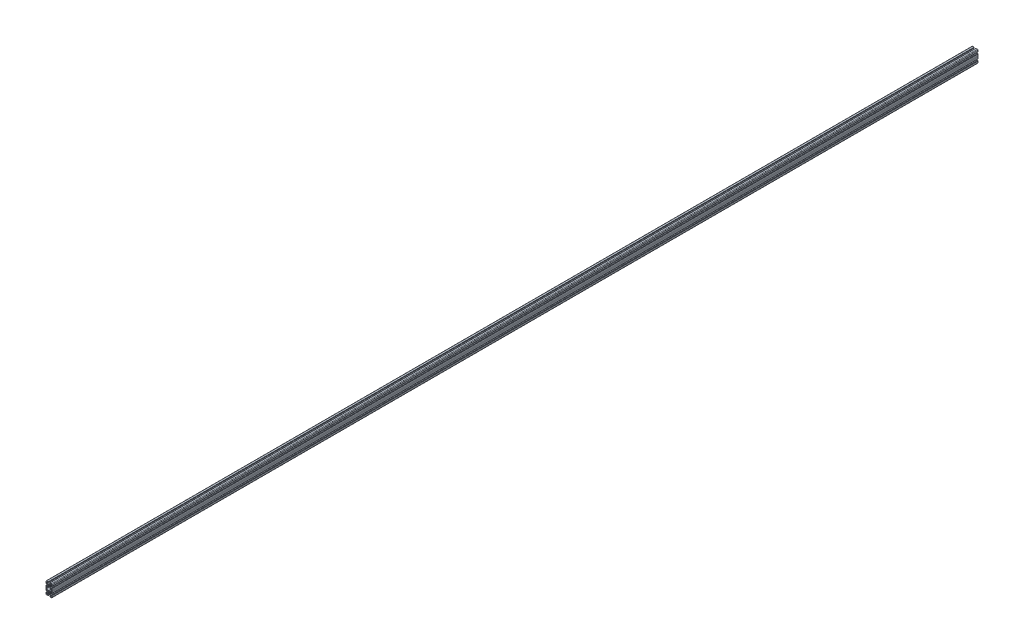
SolidWorks part; units mm, degrees
ref_plane "Front Plane" through (0, 0, 0) normal (0, 0, 1) x (1, 0, 0)
ref_plane "Top Plane" through (0, 0, 0) normal (0, 1, 0) x (1, 0, 0)
ref_plane "Right Plane" through (0, 0, 0) normal (1, 0, 0) x (0, 0, -1)
sketch "Sketch1" plane through (0, 0, 0) normal (0, 0, 1) x (1, 0, 0)
  line L0 (0, 10) -> (0, 20) construction
  line L1 (0, 10) -> (10, 10) construction
  line L2 (0, 10) -> (-10, 20) construction
  line L3 (-7.9302, 19.9988) -> (-3.2721, 19.8361)
  line L4 (-10, 20) -> (0, 20) construction
  line L6 (-2.8352, 18.0198) -> (-4.953, 18.0937)
  line L10 (0, 13.6) -> (-1.1022, 13.6)
  line L11 (-3.2236, 14.4787) -> (-5.5244, 16.7796)
  line L24 (0, 10) -> (-10, 10) construction
  line L25 (-10, 10) -> (0, 10) construction
  line L27 (-10, 0) -> (-10, 20) construction
  line L28 (0, 20) -> (10, 20) construction
  line L29 (-2.5249, 18.3091) -> (-2.5005, 19.0087)
  line L30 (-10, -20) -> (10, -20) construction
  line L31 (0, 20) -> (0, -20) construction
  arc A0 (-9.4142, 19.4142) -> (-7.9302, 19.9988) centre (-8, 18) cw
  arc A5 (-3.2721, 19.8361) -> (-2.5005, 19.0087) centre (-3.3, 19.0366) cw
  arc A6 (-1.1022, 13.6) -> (-3.2236, 14.4787) centre (-1.1022, 16.6) cw
  circle A16 centre (0, 10) radius 2.15
  arc A18 (-5.5244, 16.7796) -> (-4.953, 18.0937) centre (-4.9799, 17.3241) cw
  arc A20 (-2.8352, 18.0198) -> (-2.5249, 18.3091) centre (-2.8247, 18.3196) ccw
  point P15 (0, -20)
  point P24 (0, 0)
  point P42 (-2.3449, 13.6)
  point P80 (-10, 10)
  dimension "D11" = 2
  dimension "D15" = 3
  dimension "Center Hole Diameter" = 4.3
  dimension "D7" = 0.8
  dimension "D8" = 0.3
  dimension "D4" = 0.7701
  dimension "D1" = 45
  dimension "D2" = 2
  dimension "Rail Width" = 20
  dimension "T-Slot Depth" = 6.4
  dimension "D9" = 1.8
  dimension "D23" = 7.2
  dimension "D5" = 11.5
  dimension "T-Slot Width" = 5
  dimension "D3" = 1.775
  dimension "D6" = 9.9598
  dimension "Rail Height" = 40
sketch "Sketch2" plane through (0, 0, 0) normal (1, 0, 0) x (0, 0, -1)
  line L0 (-1524, 0) -> (1524, 0)
  line L1 (-1524, -20) -> (-1524, 20)
  line L2 (0, 10) -> (0, 20) construction
  line L3 (0, 0) -> (0, 20) construction
  line L4 (1524, -20) -> (1524, 20)
  line L5 (-10, 10) -> (10, 10) construction
  point P0 (-1491.5, 0)
  point P3 (0, 0)
  point P7 (1491.5, 0)
  point P11 (-1524, 0)
  point P14 (1524, 0)
  point P23 (0, 10)
  dimension "D1" = 32.5
  dimension "Length" = 3048
sketch "Sketch3" plane through (0, 0, 0) normal (0, 0, 1) x (1, 0, 0)
  line L0 (-2.5249, 18.3091) -> (-2.5005, 19.0087) construction
  line L1 (0, 10) -> (-10, 20) construction
  line L2 (0, 10) -> (-10, 20) construction
  line L5 (-7.9302, 19.9988) -> (-3.2721, 19.8361) construction
  line L6 (-2.8352, 18.0198) -> (-4.953, 18.0937) construction
  line L7 (-8.3091, 7.4751) -> (-9.0087, 7.4995)
  line L17 (-2.5249, 18.3091) -> (-2.5005, 19.0087)
  line L19 (-2.8352, 18.0198) -> (-4.953, 18.0937)
  line L21 (-3.6, 10) -> (0, 10) construction
  line L22 (-3.6, 8.8978) -> (-3.6, 11.1022)
  line L23 (-4.4787, 13.2236) -> (-6.7796, 15.5244)
  line L42 (-3.2236, 14.4787) -> (-5.5244, 16.7796) construction
  line L43 (0, 13.6) -> (-1.1022, 13.6) construction
  line L44 (-7.9302, 19.9988) -> (-3.2721, 19.8361)
  line L47 (-3.2236, 14.4787) -> (-5.5244, 16.7796)
  line L48 (1.1022, 13.6) -> (-1.1022, 13.6)
  line L59 (0, 13.6) -> (0, 12.15) construction
  line L60 (-9.9988, 17.9302) -> (-9.8361, 13.2721)
  line L61 (-8.0198, 12.8352) -> (-8.0937, 14.953)
  line L62 (-8.3091, 12.5249) -> (-9.0087, 12.5005)
  line L63 (-8.0198, 7.1648) -> (-8.0937, 5.047)
  line L64 (-9.9868, 2.4128) -> (-9.8361, 6.7279)
  line L65 (1.1022, 6.4) -> (-1.1022, 6.4)
  line L66 (-3.2236, 5.5213) -> (-7.3307, 1.4142)
  line L68 (-4.4787, 6.7764) -> (-6.7796, 4.4756)
  line L73 (10, 0) -> (-10, 0) construction
  line L75 (-10, 0) -> (-9.999, 1.7266)
  line L77 (10, 0) -> (9.999, 1.7266)
  line L78 (4.4787, 6.7764) -> (6.7796, 4.4756)
  line L79 (3.2236, 5.5213) -> (7.3307, 1.4142)
  line L81 (9.9868, 2.4128) -> (9.8361, 6.7279)
  line L82 (8.0198, 7.1648) -> (8.0937, 5.047)
  line L83 (8.3091, 12.5249) -> (9.0087, 12.5005)
  line L84 (8.0198, 12.8352) -> (8.0937, 14.953)
  line L85 (9.9988, 17.9302) -> (9.8361, 13.2721)
  line L87 (3.2236, 14.4787) -> (5.5244, 16.7796)
  line L88 (7.9302, 19.9988) -> (3.2721, 19.8361)
  line L89 (4.4787, 13.2236) -> (6.7796, 15.5244)
  line L90 (3.6, 8.8978) -> (3.6, 11.1022)
  line L91 (2.8352, 18.0198) -> (4.953, 18.0937)
  line L92 (2.5249, 18.3091) -> (2.5005, 19.0087)
  line L93 (8.3091, 7.4751) -> (9.0087, 7.4995)
  line L94 (-10, 0) -> (-7.9165, 0)
  line L96 (7.9165, 0) -> (10, 0)
  arc A0 (-7.9302, 19.9988) -> (-9.4142, 19.4142) centre (-8, 18) ccw construction
  arc A1 (-2.8352, 18.0198) -> (-2.5249, 18.3091) centre (-2.8247, 18.3196) ccw construction
  arc A3 (-2.8352, 18.0198) -> (-2.5249, 18.3091) centre (-2.8247, 18.3196) ccw
  arc A5 (-7.9302, 19.9988) -> (-9.9988, 17.9302) centre (-8, 18) ccw
  arc A10 (-3.2236, 5.5213) -> (-1.1022, 6.4) centre (-1.1022, 3.4) cw
  circle A13 centre (0, 10) radius 2.15 construction
  circle A14 centre (0, 10) radius 2.15
  arc A15 (-4.4787, 13.2236) -> (-3.6, 11.1022) centre (-6.6, 11.1022) cw
  arc A16 (-8.0937, 14.953) -> (-6.7796, 15.5244) centre (-7.3241, 14.9799) cw
  arc A17 (-9.0087, 12.5005) -> (-9.8361, 13.2721) centre (-9.0366, 13.3) cw
  arc A18 (-8.0198, 12.8352) -> (-8.3091, 12.5249) centre (-8.3196, 12.8247) cw
  arc A36 (-2.5005, 19.0087) -> (-3.2721, 19.8361) centre (-3.3, 19.0366) ccw construction
  arc A38 (-4.953, 18.0937) -> (-5.5244, 16.7796) centre (-4.9799, 17.3241) ccw construction
  arc A39 (-3.2236, 14.4787) -> (-1.1022, 13.6) centre (-1.1022, 16.6) ccw construction
  arc A41 (-2.5005, 19.0087) -> (-3.2721, 19.8361) centre (-3.3, 19.0366) ccw
  arc A43 (-4.953, 18.0937) -> (-5.5244, 16.7796) centre (-4.9799, 17.3241) ccw
  arc A44 (-3.2236, 14.4787) -> (-1.1022, 13.6) centre (-1.1022, 16.6) ccw
  arc A47 (-8.0198, 7.1648) -> (-8.3091, 7.4751) centre (-8.3196, 7.1753) ccw
  arc A48 (-9.0087, 7.4995) -> (-9.8361, 6.7279) centre (-9.0366, 6.7) ccw
  arc A49 (-8.0937, 5.047) -> (-6.7796, 4.4756) centre (-7.3241, 5.0201) ccw
  arc A50 (-4.4787, 6.7764) -> (-3.6, 8.8978) centre (-6.6, 8.8978) ccw
  arc A54 (-7.9165, 0) -> (-7.3307, 1.4142) centre (-5.9165, 0) cw
  arc A55 (-9.999, 1.7266) -> (-9.9868, 2.4128) centre (10.001, 1.7148) cw
  arc A56 (9.999, 1.7266) -> (9.9868, 2.4128) centre (-10.001, 1.7148) ccw
  arc A57 (7.9165, 0) -> (7.3307, 1.4142) centre (5.9165, 0) ccw
  arc A58 (4.4787, 6.7764) -> (3.6, 8.8978) centre (6.6, 8.8978) cw
  arc A59 (8.0937, 5.047) -> (6.7796, 4.4756) centre (7.3241, 5.0201) cw
  arc A60 (9.0087, 7.4995) -> (9.8361, 6.7279) centre (9.0366, 6.7) cw
  arc A61 (8.0198, 7.1648) -> (8.3091, 7.4751) centre (8.3196, 7.1753) cw
  arc A62 (3.2236, 14.4787) -> (1.1022, 13.6) centre (1.1022, 16.6) cw
  arc A63 (4.953, 18.0937) -> (5.5244, 16.7796) centre (4.9799, 17.3241) cw
  arc A64 (2.5005, 19.0087) -> (3.2721, 19.8361) centre (3.3, 19.0366) cw
  arc A65 (8.0198, 12.8352) -> (8.3091, 12.5249) centre (8.3196, 12.8247) ccw
  arc A66 (9.0087, 12.5005) -> (9.8361, 13.2721) centre (9.0366, 13.3) ccw
  arc A67 (8.0937, 14.953) -> (6.7796, 15.5244) centre (7.3241, 14.9799) ccw
  arc A68 (4.4787, 13.2236) -> (3.6, 11.1022) centre (6.6, 11.1022) ccw
  arc A70 (3.2236, 5.5213) -> (1.1022, 6.4) centre (1.1022, 3.4) ccw
  arc A71 (7.9302, 19.9988) -> (9.9988, 17.9302) centre (8, 18) cw
  arc A72 (2.8352, 18.0198) -> (2.5249, 18.3091) centre (2.8247, 18.3196) cw
  point P59 (-9.9988, 2.0698)
  point P71 (0, 0)
  point P116 (0, 6.4)
  dimension "D1" = 20
extrude "Boss-Extrude1" add sketch "Sketch3" along normal mid plane 3048
pattern_circular "CirPattern1" count 2 over 360 about axis through (0, 0, 0) along (0, 0, 1) of "Boss-Extrude1"
ref_plane "Contact Plane 1" through (0, 20, 0) normal (0, 1, 0) x (1, 0, 0)
ref_plane "Contact Plane 2" through (10, 10, 0) normal (1, 0, 0) x (0, 0, -1)
ref_plane "Contact Plane 3" through (0, -20, 0) normal (0, -1, 0) x (-1, 0, 0)
ref_plane "Contact Plane 4" through (-10, 10, 0) normal (-1, 0, 0) x (0, 0, 1)
equation "\"D1@Sketch2\"=\"Rail Width@Sketch1\"*1.625"
equation "\"D1@Boss-Extrude1\" = \"Length@Sketch2\""
equation "\"D1@Sketch3\"=\"Rail Width@Sketch1\""
